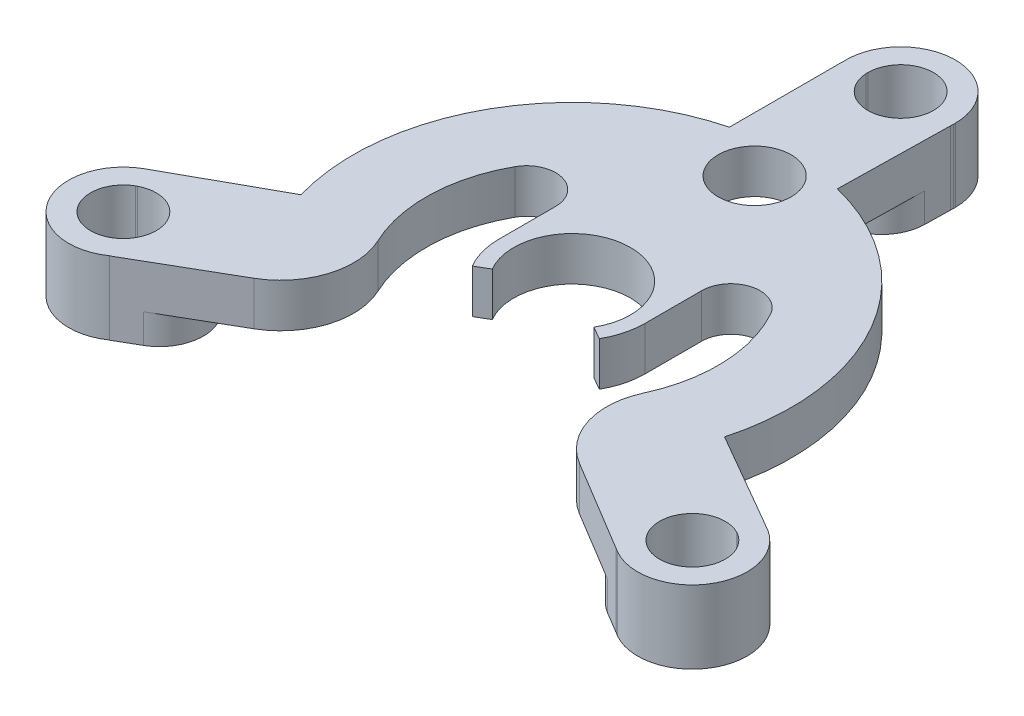
SolidWorks part; units mm, degrees
ref_plane "前视基准面" through (0, 0, 0) normal (0, 0, 1) x (1, 0, 0)
ref_plane "上视基准面" through (0, 0, 0) normal (0, 1, 0) x (1, 0, 0)
ref_plane "右视基准面" through (0, 0, 0) normal (1, 0, 0) x (0, 0, -1)
sketch "草图1" plane through (0, 0, 0) normal (0, 1, 0) x (1, 0, 0)
  line L0 (0, 20.25) -> (0, 22.5) construction
  line L1 (-2.25, 22.5) -> (-2.25, 22.3872)
  line L2 (-2.25, 0) -> (0, 0)
  line L3 (2.25, 0) -> (2.25, 1.299)
  line L4 (0, 0) -> (2.25, 0)
  line L5 (20.6106, -9.3014) -> (20.5129, -9.2451)
  line L6 (-1.125, -1.9486) -> (1.5, -3.4641)
  line L7 (1.125, 1.9486) -> (0, 0)
  line L8 (0, 0) -> (-1.125, -1.9486)
  line L9 (-18.3606, -13.1986) -> (-18.2629, -13.1422)
  line L10 (-1.125, 1.9486) -> (-3.75, 0.433)
  line L11 (1.125, -1.9486) -> (0, 0)
  line L12 (0, 0) -> (-1.125, 1.9486)
  line L13 (-3.75, 22.5) -> (-3.75, 0)
  line L14 (-3.75, 0) -> (0, 0)
  line L15 (3.75, 22.5) -> (3.344, 0)
  line L16 (3.344, 0) -> (0, 0)
  line L17 (-2.25, 1.299) -> (-2.25, 0)
  line L18 (2.25, 22.3872) -> (2.25, 22.5)
  line L19 (17.6106, -14.4976) -> (-1.672, -2.896)
  line L20 (21.3606, -8.0024) -> (1.875, 3.2476)
  line L21 (1.875, 3.2476) -> (0, 0)
  line L22 (-1.672, -2.896) -> (0, 0)
  line L23 (-21.3606, -8.0024) -> (-1.672, 2.896)
  line L24 (-17.6106, -14.4976) -> (1.875, -3.2476)
  line L25 (1.875, -3.2476) -> (0, 0)
  line L26 (-1.672, 2.896) -> (0, 0)
  line L27 (-20.5129, -9.2451) -> (-20.6106, -9.3014)
  line L28 (-1.1059, -3.2366) -> (1.125, -1.9486)
  line L29 (3.3559, 0.6606) -> (1.125, 1.9486)
  line L30 (18.2629, -13.1422) -> (18.3606, -13.1986)
  circle A1 centre (0, 0) radius 22.5
  circle A2 centre (0, 22.5) radius 2.25
  circle A3 centre (19.4856, -11.25) radius 2.25
  circle A4 centre (-19.4856, -11.25) radius 2.25
  circle A5 centre (0, 22.5) radius 3.75
  arc A6 (17.3465, -14.33) -> (21.0834, -7.8575) centre (19.4856, -11.25) ccw
  arc A7 (-21.0834, -7.8575) -> (-17.3465, -14.33) centre (-19.4856, -11.25) ccw
  point P24 (0, 0)
  point P47 (0, 0)
  dimension "D1" = 3
  dimension "D2" = 45
  dimension "D3" = 4.5
  dimension "D4" = 7.5
  dimension "D5" = 3
extrude "凸台-拉伸1" add sketch "草图1" along normal blind 5 contours A5 A1 L13 L23 L26 L12 L7 L21 L20 L15 | L29 L15 L20 L21 | L3 L29 L7 L4 | L15 L29 L3 L16 | L17 L10 L13 L14 | L26 L23 L13 L10 | L10 L17 L2 L12 | A1 A5 L15 L1 A2 L18 | A1 A5 A2 | A3 A1 L20 L15 L16 L4 L11 L25 L24 L19 | A6 A1 L5 A3 L30 L19 | L6 L28 L11 L8 | L28 L6 L24 L25 | L28 L19 L24 L6 | L19 L28 L6 L22 | A4 A1 L24 L19 L22 L8 L2 L14 L13 L23 | A7 A1 L9 A4 L27 L23
sketch "草图2" plane through (0, 0, 0) normal (0, -1, 0) x (1, 0, 0)
  circle A0 centre (0, 0) radius 17.5
  dimension "D1" = 35
extrude "切除-拉伸1" cut sketch "草图2" against normal blind 2
fillet "圆角1" radius 3 6 edges at (-3.75, 1, -17.0935) (3.6528, 1, -17.1145) (-16.648, 1, 5.3938) (-12.9284, 1, 11.7943) (12.9952, 1, 11.7207) (16.6784, 1, 5.2992)
sketch "草图3" plane through (0, 5, 0) normal (0, 1, 0) x (1, 0, 0)
  line L0 (-14.4126, -4.1565) -> (-9.8648, -1.639)
  line L1 (-21.086, -7.8504) -> (-3.75, 1.7457) construction
  line L2 (9.9033, -1.3875) -> (14.4529, -4.0142)
  line L3 (21.088, -7.8451) -> (3.3868, 2.3747) construction
  circle A0 centre (0, 0) radius 15
  circle A1 centre (0, 0) radius 10
  line M12 (21.088, -7.8451) -> (3.3868, 2.3747)
  line M13 (3.3868, 2.3747) -> (3.7443, 22.1863)
  line M19 (-3.75, 22.1853) -> (-3.75, 1.7457)
  line M20 (-3.75, 1.7457) -> (-21.086, -7.8504)
  dimension "D1" = 30
  dimension "D2" = 5
extrude "凸台-拉伸2" add sketch "草图3" against normal blind 3 contours A1 A0 M12 M13 | A1 A0 M19 M20
sketch "草图4" plane through (0, 5, 0) normal (0, 1, 0) x (1, 0, 0)
  circle A1 centre (0, 0) radius 10
extrude "切除-拉伸2" cut sketch "草图4" against normal blind 3
fillet "圆角2" radius 5 2 edges at (-6.1533, 3.5, 7.8827) (6.3518, 3.5, 7.7236)
sketch "草图5" plane through (0, 5, 0) normal (0, 1, 0) x (1, 0, 0)
  line L0 (0, 0) -> (-0.046, 9.9999) construction
  line L1 (-4, 0) -> (-4, 9.1652)
  line L2 (4, 0) -> (4, 9.1652)
  line L3 (0, 0) -> (-6.3338, -3.6957)
  line L4 (0, 0) -> (6.2796, -3.5872)
  line L5 (-5, 0) -> (-5, 8.6603)
  line L6 (5, 8.6603) -> (5, 0)
  arc A0 (9.0856, -4.1776) -> (-9.0468, -4.2609) centre (0, 0) ccw construction
  circle A1 centre (0, 0) radius 4
  arc A2 (4, 9.1652) -> (-4, 9.1652) centre (0, 0) ccw
  circle A3 centre (0, 0) radius 5
  arc M8 (-9.0468, -4.2609) -> (9.0856, -4.1776) centre (0, 0) cw
  dimension "D1" = 8
  dimension "D2" = 10
  dimension "D3" = 120
  dimension "D4" = 120
extrude "凸台-拉伸3" add sketch "草图5" against normal blind 3 contours L1 A3 L3 A1 | A3 L1 L5 M8 | A3 L0 L1 M8 | A1 L0 A3 L1 | L0 A3 L2 A2 | L0 A1 L2 A3 | A3 L6 L2 M8 | A3 L2 A1 L4
fillet "圆角3" radius 2 2 edges at (5, 3.5, -8.6603) (-5, 3.5, -8.6603)
sketch "草图6" plane through (0, 5, 0) normal (0, 1, 0) x (1, 0, 0)
  circle A0 centre (0, 12.5) radius 2.5
  arc A1 (-2.2472, 22.3875) -> (2.2472, 22.3875) centre (0, 22.5) ccw construction
  dimension "D1" = 5
  dimension "D2" = 10
extrude "切除-拉伸3" cut sketch "草图6" against normal blind 3
